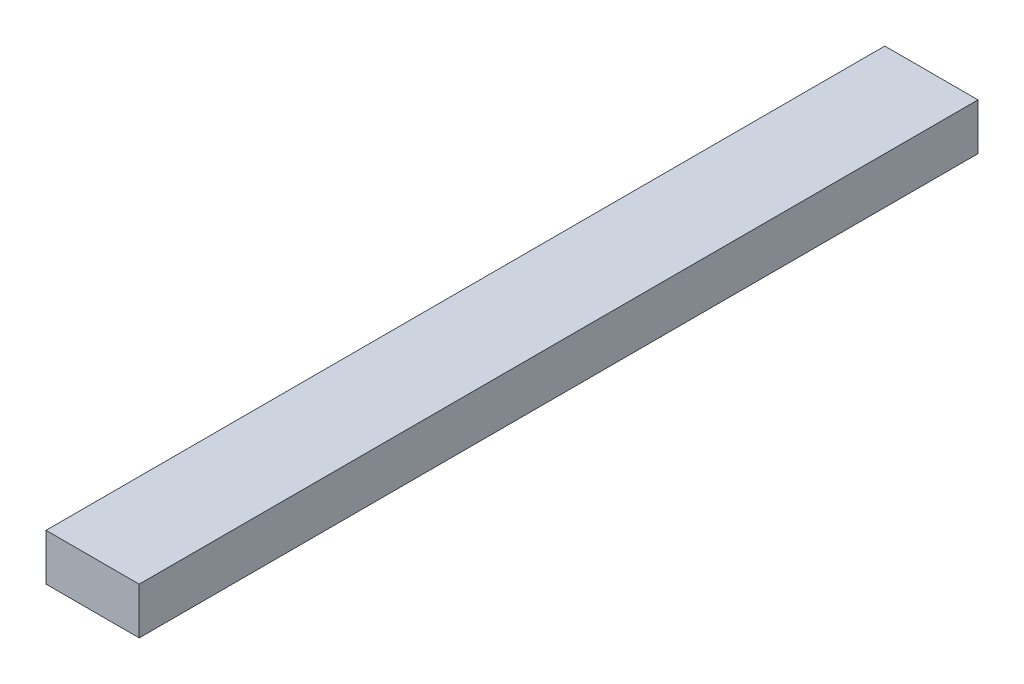
SolidWorks part; units mm, degrees
ref_plane "Front Plane" through (0, 0, 0) normal (0, 0, 1) x (1, 0, 0)
ref_plane "Top Plane" through (0, 0, 0) normal (0, 1, 0) x (1, 0, 0)
ref_plane "Right Plane" through (0, 0, 0) normal (1, 0, 0) x (0, 0, -1)
sketch "Sketch1" plane through (0, 0, 0) normal (0, 0, 1) x (1, 0, 0)
  line L1 (0, 0) -> (101.6, 0)
  line L2 (0, 0) -> (0, 50.8)
  line L3 (0, 50.8) -> (101.6, 50.8)
  line L4 (101.6, 0) -> (101.6, 50.8)
  dimension "D1" = 50.8
  dimension "D2" = 101.6
extrude "Boss-Extrude1" add sketch "Sketch1" along normal blind 914.4
